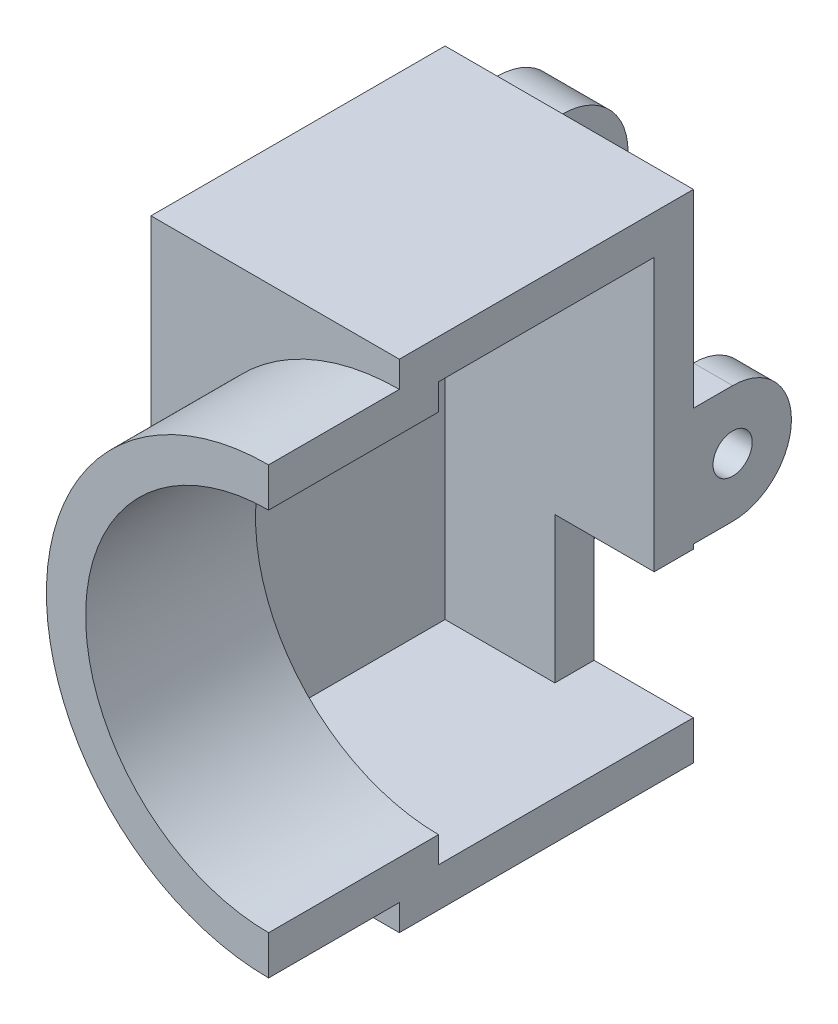
SolidWorks part; units mm, degrees
material "ABS"
ref_plane "前视基准面" through (0, 0, 0) normal (0, 0, 1) x (1, 0, 0)
ref_plane "上视基准面" through (0, 0, 0) normal (0, 1, 0) x (1, 0, 0)
ref_plane "右视基准面" through (0, 0, 0) normal (1, 0, 0) x (0, 0, -1)
sketch "草图1" plane through (0, 0, 0) normal (0, 0, 1) x (1, 0, 0)
  circle A0 centre (0, 0) radius 14
  circle A1 centre (0, 0) radius 17
  dimension "D1" = 28
  dimension "D2" = 34
extrude "凸台-拉伸1" add sketch "草图1" along normal blind 10
sketch "草图2" plane through (0, 0, 0) normal (0, 0, -1) x (-1, 0, 0)
  line L1 (19, 19) -> (-19, 19)
  line L2 (19, 19) -> (19, -19)
  line L3 (19, -19) -> (-19, -19)
  line L4 (-19, 19) -> (-19, -19)
  line L5 (0, -19) -> (0, 19) construction
  line L6 (19, 0) -> (-19, 0) construction
  point P0 (0, 0)
  dimension "D1" = 38
  dimension "D2" = 38
extrude "凸台-拉伸2" add sketch "草图2" along normal blind 22.5
sketch "草图3" plane through (0, 0, -22.5) normal (0, 0, -1) x (-1, 0, 0)
  line L1 (16, 16) -> (-16, 16)
  line L2 (16, 16) -> (16, -16)
  line L3 (16, -16) -> (-16, -16)
  line L4 (-16, 16) -> (-16, -16)
  line L5 (0, -16) -> (0, 16) construction
  line L6 (16, 0) -> (-16, 0) construction
  point P0 (0, 0)
  dimension "D1" = 32
  dimension "D2" = 32
extrude "切除-拉伸1" cut sketch "草图3" against normal blind 19.5
sketch "草图4" plane through (0, 0, 0) normal (0, 0, 1) x (1, 0, 0)
  circle A1 centre (0, 0) radius 14
  circle A2 centre (0, 0) radius 14
  dimension "D1" = 0
extrude "切除-拉伸2" cut sketch "草图4" against normal through all
sketch "草图5" plane through (0, 0, -22.5) normal (0, 0, -1) x (-1, 0, 0)
  line L1 (-4.5, -16) -> (7.6, -16)
  line L2 (-4.5, -16) -> (-4.5, -4.84)
  line L3 (-4.5, -4.84) -> (7.6, -4.84)
  line L4 (-19, 19) -> (-19, -19)
  line L5 (-19, -19) -> (19, -19)
  line L6 (19, -19) -> (19, 19)
  line L7 (19, 19) -> (-19, 19)
  line L8 (-19, 19) -> (-19, -19)
  line L9 (-19, -19) -> (19, -19)
  line L10 (19, -19) -> (19, 19)
  line L11 (19, 19) -> (-19, 19)
  line L12 (7.6, -16) -> (7.6, -4.84)
  line L13 (-16, 16) -> (-16, -16) construction
  line L15 (16, -16) -> (16, 16) construction
  line L16 (-16, -16) -> (16, -16) construction
  line L17 (-16, -16) -> (16, -16) construction
  dimension "D2" = 11.5
  dimension "D3" = 8.4
  dimension "D4" = 11.16
  dimension "D1" = 0
extrude "凸台-拉伸3" add sketch "草图5" against normal blind 3
sketch "草图6" plane through (0, 0, 0) normal (1, 0, 0) x (0, 0, -1)
  line L0 (22.5, 4.5) -> (25.5, 4.5)
  line L1 (22.5, 19) -> (22.5, -19) construction
  line L2 (25.5, -4.5) -> (22.5, -4.5)
  line L3 (22.5, -4.5) -> (22.5, 4.5)
  arc A0 (25.5, 4.5) -> (25.5, -4.5) centre (25.5, 0) cw
  circle A1 centre (25.5, 0) radius 1.5
  dimension "D3" = 3
  dimension "D1" = 3
  dimension "D2" = 9
extrude "凸台-拉伸4" add sketch "草图6" along normal mid plane 6
sketch "草图7" plane through (19, 0, 0) normal (1, 0, 0) x (0, 0, -1)
  line L0 (22.5, 15) -> (26.5, 15)
  line L1 (22.5, 19) -> (22.5, -19) construction
  line L2 (26.5, 5) -> (22.5, 5)
  line L3 (22.5, 5) -> (22.5, 15)
  line L4 (-15.6353, 0) -> (39.5425, 0) construction
  line L5 (22.5, -5) -> (22.5, -15)
  line L6 (26.5, -5) -> (22.5, -5)
  line L7 (22.5, -15) -> (26.5, -15)
  arc A0 (26.5, 15) -> (26.5, 5) centre (26.5, 10) cw
  circle A1 centre (26.5, 10) radius 1.5
  circle A2 centre (26.5, -10) radius 1.5
  arc A3 (26.5, -15) -> (26.5, -5) centre (26.5, -10) ccw
  dimension "D1" = 3
  dimension "D3" = 5
  dimension "D2" = 10
  dimension "D4" = 4
extrude "凸台-拉伸5" add sketch "草图7" against normal blind 5
sketch "草图8" plane through (14, 0, 0) normal (-1, 0, 0) x (0, 0, 1)
  line L0 (-46.7529, 0) -> (17.6956, 0) construction
  line L1 (-26.5, 6.8246) -> (-23.75, 8.4123)
  line L2 (-23.75, 8.4123) -> (-23.75, 11.5877)
  line L3 (-23.75, 11.5877) -> (-26.5, 13.1754)
  line L4 (-26.5, 13.1754) -> (-29.25, 11.5877)
  line L5 (-29.25, 11.5877) -> (-29.25, 8.4123)
  line L6 (-29.25, 8.4123) -> (-26.5, 6.8246)
  line L7 (-29.25, -8.4123) -> (-26.5, -6.8246)
  line L8 (-29.25, -11.5877) -> (-29.25, -8.4123)
  line L9 (-26.5, -13.1754) -> (-29.25, -11.5877)
  line L10 (-23.75, -11.5877) -> (-26.5, -13.1754)
  line L11 (-23.75, -8.4123) -> (-23.75, -11.5877)
  line L12 (-26.5, -6.8246) -> (-23.75, -8.4123)
  circle A0 centre (-26.5, 10) radius 2.75 construction
  circle A1 centre (-26.5, -10) radius 2.75 construction
  dimension "D1" = 5.5
extrude "切除-拉伸3" cut sketch "草图8" against normal blind 2
mirror "镜向1" about plane through (0, 0, 0) normal (1, 0, 0) of "凸台-拉伸5", "切除-拉伸3"
sketch "草图9" plane through (0, 0, -22.5) normal (0, 0, -1) x (-1, 0, 0)
  line L1 (0, 27.5974) -> (-32.496, 27.5974)
  line L2 (0, 27.5974) -> (0, -27.9906)
  line L3 (0, -27.9906) -> (-32.496, -27.9906)
  line L4 (-32.496, 27.5974) -> (-32.496, -27.9906)
extrude "切除-拉伸5" cut sketch "草图9" against normal through all and the other way through all contours L4 L3 L2 L1
